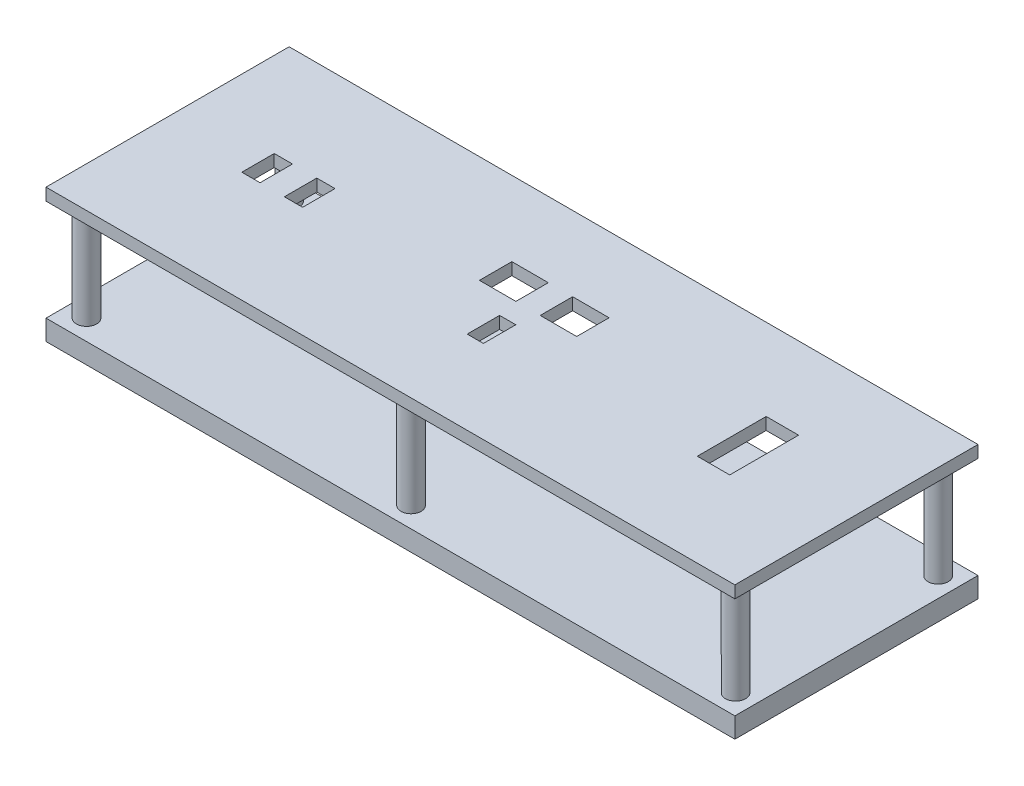
SolidWorks part; units mm, degrees
ref_plane "前视基准面" through (0, 0, 0) normal (0, 0, 1) x (1, 0, 0)
ref_plane "上视基准面" through (0, 0, 0) normal (0, 1, 0) x (1, 0, 0)
ref_plane "右视基准面" through (0, 0, 0) normal (1, 0, 0) x (0, 0, -1)
sketch "草图1" plane through (0, 0, 0) normal (0, 1, 0) x (1, 0, 0)
  line L0 (-55.4478, 71.655) -> (-55.4478, -89.8737) construction
  line L1 (-55.4478, 29.2897) -> (114.5522, 29.2897)
  line L2 (-55.4478, 29.2897) -> (-55.4478, -30.7103)
  line L3 (-55.4478, -30.7103) -> (114.5522, -30.7103)
  line L4 (114.5522, 29.2897) -> (114.5522, -30.7103)
  line L5 (1.2222, 71.655) -> (1.2222, -89.8737) construction
  line L6 (57.8922, 71.655) -> (57.8922, -89.8737) construction
  line L7 (114.5622, 71.655) -> (114.5622, -89.8737) construction
  line L8 (-1055.3077, 0.6408) -> (49944.6923, 0.6408) construction
  line L9 (-34.4727, 0.6408) -> (-19.4727, 0.6408) construction
  line L10 (-34.4727, -3.3592) -> (-29.9727, -3.3592)
  line L11 (-34.4727, 4.6408) -> (-29.9727, 4.6408)
  line L12 (-26.9727, 1036.6911) -> (-26.9727, -49963.3089) construction
  line L13 (-34.4727, 4.6408) -> (-34.4727, -3.3592)
  line L16 (-19.4727, 4.6408) -> (-19.4727, -3.3592)
  line L18 (57.8922, 0.6408) -> (114.5522, 0.6408) construction
  line L19 (86.4282, -999.3592) -> (86.4282, 1036.8281) construction
  line L20 (82.4282, -7.8592) -> (82.4282, 9.1408)
  line L21 (82.4282, 9.1408) -> (90.4282, 9.1408)
  line L22 (90.4282, -7.8592) -> (90.4282, 9.1408)
  line L23 (82.4282, -7.8592) -> (90.4282, -7.8592)
  line L24 (84.4282, 6.1408) -> (88.4282, 6.1408) construction
  line L26 (11.8883, -2.1509) -> (51.3032, -2.1509) construction
  line L27 (27.9333, -2.1509) -> (31.9333, -2.1509)
  line L28 (80.9282, 10.6408) -> (91.9282, 10.6408) construction
  line L29 (27.9333, -2.1509) -> (27.9333, -10.1509)
  line L30 (27.9333, -10.1509) -> (31.9333, -10.1509)
  line L31 (31.9333, -2.1509) -> (31.9333, -10.1509)
  line L32 (29.9555, 1037.3138) -> (29.9555, -49962.6862) construction
  line L33 (88.4282, -4.8592) -> (88.4282, 6.1408) construction
  line L34 (84.4282, -4.8592) -> (88.4282, -4.8592) construction
  line L35 (84.4282, -4.8592) -> (84.4282, 6.1408) construction
  line L36 (11.8883, 2.8491) -> (26.9555, 2.8491) construction
  line L37 (11.8883, 10.8491) -> (26.9555, 10.8491) construction
  line L38 (91.9282, -9.3592) -> (91.9282, 10.6408) construction
  line L39 (80.9282, -9.3592) -> (80.9282, 10.6408) construction
  line L40 (80.9282, -9.3592) -> (91.9282, -9.3592) construction
  line L41 (17.9555, 29.2897) -> (17.9555, -30.7103) construction
  line L42 (41.9555, 29.2897) -> (41.9555, -30.7103) construction
  line L43 (17.9555, 1037.3138) -> (17.9555, -49962.6862) construction
  line L44 (17.9555, 10.8491) -> (26.9555, 10.8491)
  line L45 (17.9555, 10.8491) -> (17.9555, 2.8491)
  line L46 (17.9555, 2.8491) -> (26.9555, 2.8491)
  line L47 (41.9555, 10.8491) -> (41.9555, 2.8491)
  line L48 (41.9555, 1037.3138) -> (41.9555, -49962.6862) construction
  line L51 (-29.9727, 4.6408) -> (-29.9727, -3.3592)
  line L52 (32.9555, 10.8491) -> (51.3032, 10.8491) construction
  line L53 (-23.9727, 4.6408) -> (-19.4727, 4.6408)
  line L54 (-34.4727, 4.6408) -> (-19.4727, 4.6408) construction
  line L55 (11.8883, 10.8491) -> (51.3032, 10.8491) construction
  line L56 (-23.9727, -3.3592) -> (-19.4727, -3.3592)
  line L57 (-34.4727, -3.3592) -> (-19.4727, -3.3592) construction
  line L58 (32.9555, 10.8491) -> (41.9555, 10.8491)
  line L59 (26.9555, 10.8491) -> (26.9555, 2.8491)
  line L60 (-23.9727, 4.6408) -> (-23.9727, -3.3592)
  line L62 (32.9555, 10.8491) -> (32.9555, 2.8491)
  line L64 (32.9555, 2.8491) -> (51.3032, 2.8491) construction
  line L65 (11.8883, 2.8491) -> (51.3032, 2.8491) construction
  line L66 (32.9555, 2.8491) -> (41.9555, 2.8491)
  dimension "D1" = 4
  dimension "D5" = 5
  dimension "D2" = 4
  dimension "D3" = 4
  dimension "D4" = 1.5
  dimension "D6" = 8
  dimension "D7" = 12
  dimension "D8" = 12
extrude "凸台-拉伸1" add sketch "草图1" along normal blind 3
sketch "草图2" plane through (0, 0, 0) normal (0, -1, 0) x (1, 0, 0)
  line L0 (-55.4478, 30.7103) -> (-55.4478, -49969.2897) construction
  line L1 (114.5522, 30.7103) -> (114.5522, -49969.2897) construction
  line L2 (114.5522, 30.7103) -> (-49885.4478, 30.7103) construction
  line L3 (-55.4478, -29.2897) -> (49944.5522, -29.2897) construction
  line L4 (-55.4478, -24.2897) -> (49944.5522, -24.2897) construction
  line L5 (114.5522, 25.7103) -> (-49885.4478, 25.7103) construction
  line L6 (-50.4478, 30.7103) -> (-50.4478, -49969.2897) construction
  line L7 (109.5522, 30.7103) -> (109.5522, -49969.2897) construction
  line L8 (-50.4478, 25.7103) -> (109.7211, 25.7103) construction
  circle A0 centre (-50.4478, 25.7103) radius 2.5
  circle A1 centre (-50.4478, -24.2897) radius 2.5
  circle A2 centre (109.7211, -24.2897) radius 2.5
  circle A3 centre (109.7211, 25.7103) radius 2.5
  circle A4 centre (29.6366, 25.7103) radius 2.5
  circle A5 centre (29.6366, -24.2897) radius 2.5
  dimension "D1" = 5
  dimension "D2" = 5
  dimension "D3" = 5
  dimension "D4" = 5
extrude "凸台-拉伸2" add sketch "草图2" along normal blind 25
sketch "草图3" plane through (0, -25, 0) normal (0, -1, 0) x (1, 0, 0)
  line L1 (-55.4478, 30.7103) -> (114.5522, 30.7103)
  line L2 (-55.4478, 30.7103) -> (-55.4478, -29.2897)
  line L3 (-55.4478, -29.2897) -> (114.5522, -29.2897)
  line L4 (114.5522, 30.7103) -> (114.5522, -29.2897)
extrude "凸台-拉伸3" add sketch "草图3" along normal blind 5
